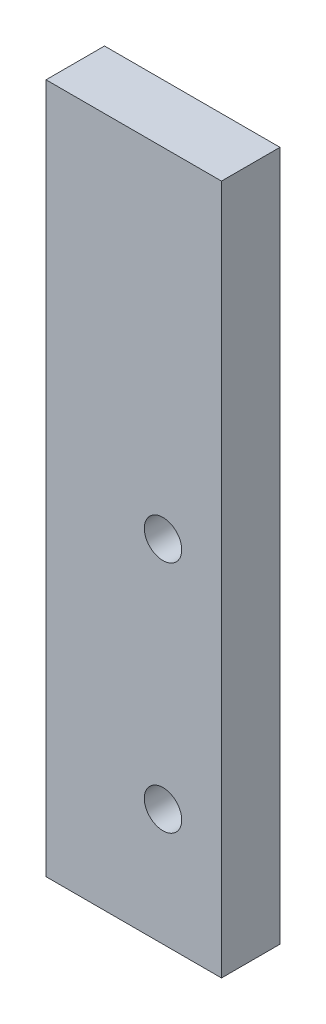
SolidWorks part; units mm, degrees
ref_plane "前视基准面" through (0, 0, 0) normal (0, 0, 1) x (1, 0, 0)
ref_plane "上视基准面" through (0, 0, 0) normal (0, 1, 0) x (1, 0, 0)
ref_plane "右视基准面" through (0, 0, 0) normal (1, 0, 0) x (0, 0, -1)
other "Configuration Table"
sketch "草图1" plane through (0, 0, 0) normal (0, 0, 1) x (1, 0, 0)
  line L1 (0, 0) -> (15, 0)
  line L2 (0, 0) -> (0, 59)
  line L3 (0, 59) -> (15, 59)
  line L4 (15, 0) -> (15, 59)
  dimension "D1" = 15
  dimension "D2" = 59
extrude "凸台-拉伸1" add sketch "草图1" along normal blind 5
sketch "草图2" plane through (0, 0, 5) normal (0, 0, 1) x (1, 0, 0)
  line L0 (10, 59) -> (10, 0) construction
  line L1 (15, 59) -> (0, 59) construction
  line L2 (0, 0) -> (15, 0) construction
  line L3 (15, 0) -> (15, 59) construction
  circle A0 centre (10, 10) radius 1.6
  circle A1 centre (10, 30) radius 1.6
  dimension "D2" = 20
  dimension "D3" = 10
  dimension "D4" = 3.2
  dimension "D1" = 5
extrude "切除-拉伸1" cut sketch "草图2" against normal blind 5
